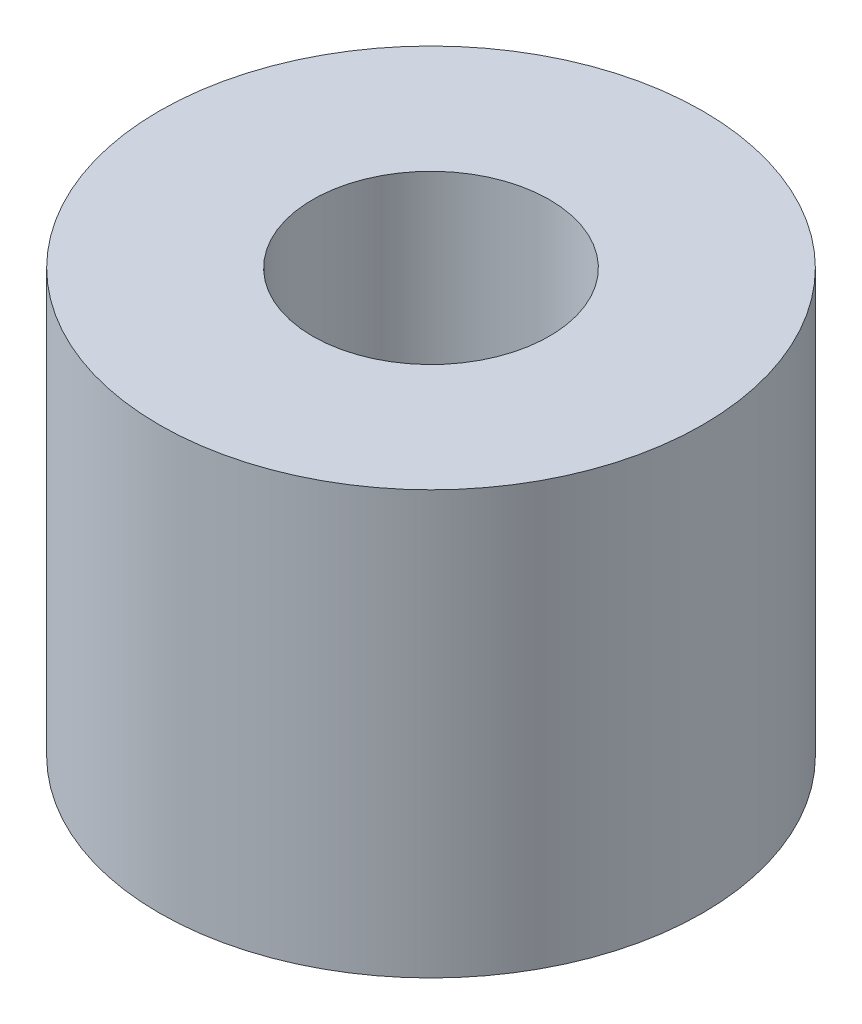
SolidWorks part; units mm, degrees
ref_plane "Front Plane" through (0, 0, 0) normal (0, 0, 1) x (1, 0, 0)
ref_plane "Top Plane" through (0, 0, 0) normal (0, 1, 0) x (1, 0, 0)
ref_plane "Right Plane" through (0, 0, 0) normal (1, 0, 0) x (0, 0, -1)
sketch "Sketch1" plane through (0, 0, 0) normal (0, 1, 0) x (1, 0, 0)
  circle A0 centre (0, 0) radius 2.4892
  circle A1 centre (0, 0) radius 5.715
  dimension "D1" = 4.9784
  dimension "D2" = 11.43
extrude "Boss-Extrude1" add sketch "Sketch1" along normal blind 8.89
